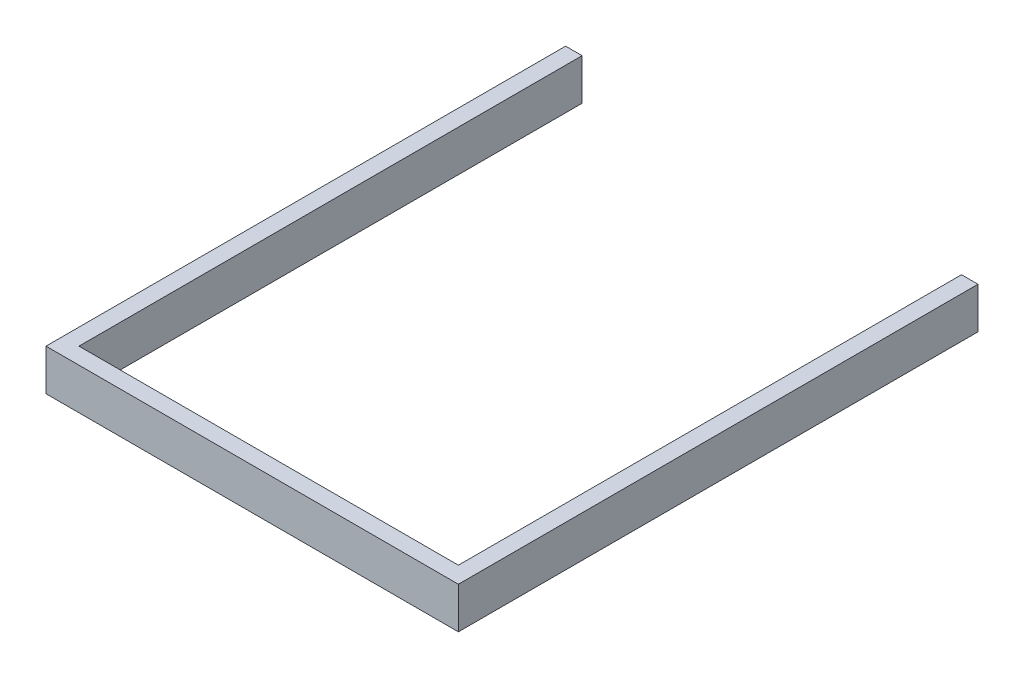
SolidWorks part; units mm, degrees
ref_plane "Front Plane" through (0, 0, 0) normal (0, 0, 1) x (1, 0, 0)
ref_plane "Top Plane" through (0, 0, 0) normal (0, 1, 0) x (1, 0, 0)
ref_plane "Right Plane" through (0, 0, 0) normal (1, 0, 0) x (0, 0, -1)
sketch "Sketch1" plane through (0, 0, 0) normal (0, 1, 0) x (1, 0, 0)
  line L1 (26, 79) -> (46, 79)
  line L2 (-46, 43) -> (-46, -79)
  line L3 (-46, -79) -> (46, -79)
  line L4 (46, 79) -> (46, -79)
  line L5 (-46, 79) -> (46, -79) construction
  line L6 (-46, -79) -> (46, 79) construction
  line L10 (26, 79) -> (26, 43) construction
  line L11 (26, 43) -> (-46, 43) construction
  line L12 (26, 83) -> (50, 83)
  line L13 (50, 83) -> (50, -83)
  line L14 (-50, -83) -> (50, -83)
  line L15 (-50, 43) -> (-50, -83)
  line L16 (46, 43) -> (50, 43)
  line L17 (26, 79) -> (26, 83)
  line L18 (-46, 43) -> (-50, 43)
  point P0 (0, 0)
  dimension "D1" = 92
  dimension "D2" = 158
  dimension "D3" = 20
  dimension "D4" = 36
  dimension "D5" = 79
  dimension "D6" = 46
  dimension "D7" = 4
extrude "DISPLAY SUPPORT" add sketch "Sketch1" against normal blind 10 contours L2 L18 L15 L14 L13 L16 L4 L3
